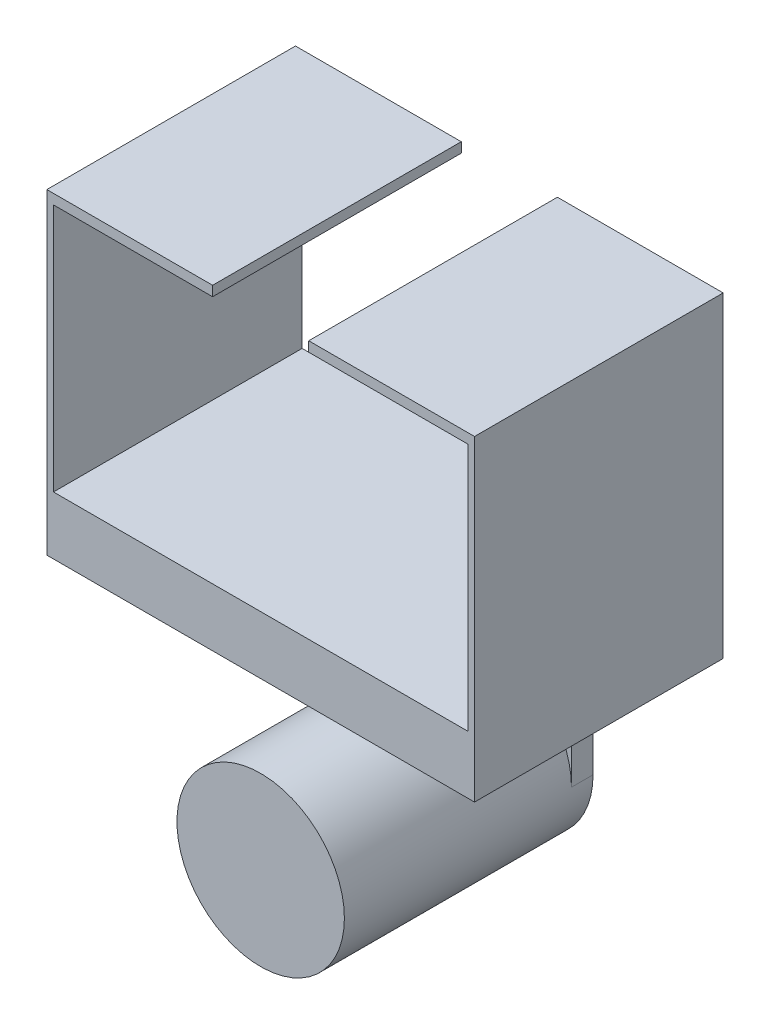
SolidWorks part; units mm, degrees
ref_plane "Front Plane" through (0, 0, 0) normal (0, 0, 1) x (1, 0, 0)
ref_plane "Top Plane" through (0, 0, 0) normal (0, 1, 0) x (1, 0, 0)
ref_plane "Right Plane" through (0, 0, 0) normal (1, 0, 0) x (0, 0, -1)
sketch "Sketch1" plane through (0, 0, 0) normal (0, 0, 1) x (1, 0, 0)
  line L0 (0, -55) -> (0, 55) construction
  circle A0 centre (0, -30.1018) radius 12.827
  dimension "D1" = 25.654
extrude "Boss-Extrude1" add sketch "Sketch1" along normal blind 38.1
sketch "Sketch2" plane through (0, 0, 0) normal (0, 0, 1) x (1, 0, 0)
  line L1 (-12.827, -30.1018) -> (12.827, -30.1018)
  line L2 (-12.827, -30.1018) -> (-12.827, -4.7018)
  line L3 (-12.827, -4.7018) -> (12.827, -4.7018)
  line L4 (12.827, -30.1018) -> (12.827, -4.7018)
  circle A0 centre (0, -30.1018) radius 12.827 construction
  dimension "D1" = 25.4
  dimension "DA" = 25.654
extrude "Boss-Extrude2" add sketch "Sketch2" along normal blind 3.302
sketch "Sketch8" plane through (0, -4.7018, 0) normal (0, 1, 0) x (1, 0, 0)
  line L0 (0, -14.1097) -> (0, 14.1097) construction
  line L1 (-31.75, 0) -> (31.75, 0)
  line L2 (-31.75, 0) -> (-31.75, -38.1)
  line L3 (-31.75, -38.1) -> (31.75, -38.1)
  line L4 (31.75, 0) -> (31.75, -38.1)
  dimension "D1" = 63.5
  dimension "D2" = 31.75
  dimension "D3" = 38.1
extrude "Boss-Extrude6" add sketch "Sketch8" along normal blind 8.89
sketch "Sketch10" plane through (31.75, 0, 0) normal (1, 0, 0) x (0, 0, -1)
  line L1 (-38.1, -4.7018) -> (0, -4.7018)
  line L2 (-38.1, -4.7018) -> (-38.1, 42.2882)
  line L3 (-38.1, 42.2882) -> (0, 42.2882)
  line L4 (0, -4.7018) -> (0, 42.2882)
  dimension "D1" = 46.99
extrude "Boss-Extrude7" add sketch "Sketch10" along normal blind 1.016
sketch "Sketch11" plane through (-31.75, 0, 0) normal (-1, 0, 0) x (0, 0, 1)
  line L0 (0, -25.9143) -> (0, 25.9143) construction
  line L1 (38.1, -4.7018) -> (0, -4.7018)
  line L2 (38.1, -4.7018) -> (38.1, 42.2882)
  line L3 (38.1, 42.2882) -> (0, 42.2882)
  line L4 (0, -4.7018) -> (0, 42.2882)
  dimension "D1" = 46.99
extrude "Boss-Extrude8" add sketch "Sketch11" along normal blind 1.016
sketch "Sketch13" plane through (0, 42.2882, 0) normal (0, 1, 0) x (1, 0, 0)
  line L0 (-25.9143, 0) -> (25.9143, 0) construction
  line L1 (32.766, -38.1) -> (7.366, -38.1)
  line L2 (32.766, -38.1) -> (32.766, 0)
  line L3 (32.766, 0) -> (7.366, 0)
  line L4 (7.366, -38.1) -> (7.366, 0)
  dimension "D1" = 25.4
extrude "Boss-Extrude9" add sketch "Sketch13" along normal blind 1.524
sketch "Sketch14" plane through (0, 42.2882, 0) normal (0, 1, 0) x (1, 0, 0)
  line L1 (-32.766, -38.1) -> (-7.366, -38.1)
  line L2 (-32.766, -38.1) -> (-32.766, 0)
  line L3 (-32.766, 0) -> (-7.366, 0)
  line L4 (-7.366, -38.1) -> (-7.366, 0)
  dimension "D1" = 25.4
extrude "Boss-Extrude10" add sketch "Sketch14" along normal blind 1.524
equation "\"F\"= 600"
equation "\"Sy\" = 36000"
equation "\"SF\" = 4"
equation "\"def\" = 0.005in"
equation "\"W\" = \"F\" * 2"
equation "\"LA\"= 1.5in"
equation "\"LB\" = \"LA\" / 3"
equation "\"a\"= 0.498in"
equation "\"b\"= 0.9992in"
equation "\"c\"= 1.499in"
equation "\"WC\"= \"a\" + 2 * \"b\""
equation "\"M_A\"= \"W\" * ( \"LA\" / 2 )"
equation "\"Z_A\" = \"M_A\" * ( \"SF\" / \"Sy\" )"
equation "\"D_A\"= 2 * ( 4 * \"Z_A\" / pi ) ^ ( 1 / 3 )"
equation "\"WB\" = \"D_A\""
equation "\"AB\"= \"W\" * \"SF\" / \"Sy\""
equation "\"HB\"= \"AB\" / \"WB\""
equation "\"MC\" = \"W\" * \"LA\" / 4"
equation "\"Z_C\"= \"MC\" * \"SF\" / \"Sy\""
equation "\"HC\"= ( 6 * \"Z_C\" / \"WC\" ) ^ ( 1 / 2 )"
equation "\"HD\"= \"c\""
equation "\"AD\"= \"F\" * \"SF\" / \"Sy\""
equation "\"WD\"= \"AD\" / \"HD\""
equation "\"WE\" = \"b\" + \"WD\""
equation "\"AE\" = \"F\" * \"SF\" / \"Sy\""
equation "\"HE\"= \"AE\" / \"WE\""
